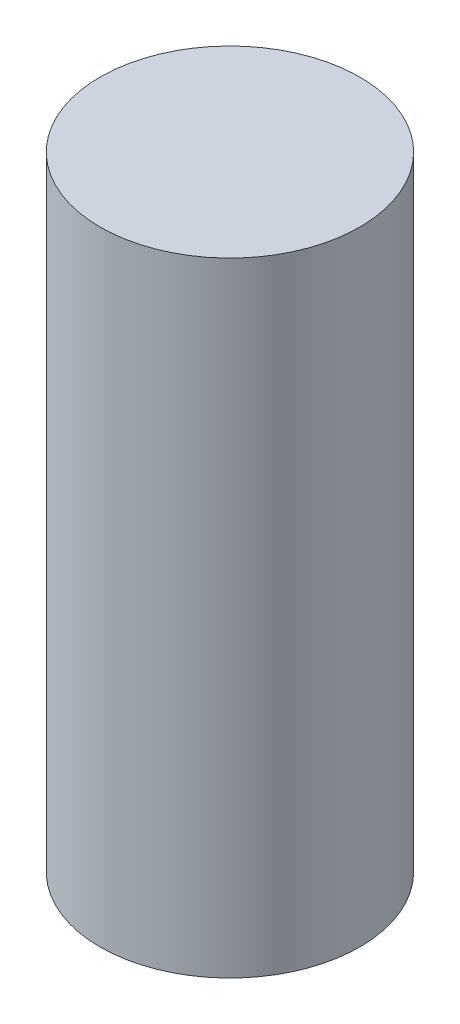
SolidWorks part; units mm, degrees
ref_plane "Front Plane" through (0, 0, 0) normal (0, 0, 1) x (1, 0, 0)
ref_plane "Top Plane" through (0, 0, 0) normal (0, 1, 0) x (1, 0, 0)
ref_plane "Right Plane" through (0, 0, 0) normal (1, 0, 0) x (0, 0, -1)
sketch "Sketch1" plane through (0, 0, 0) normal (0, 1, 0) x (1, 0, 0)
  circle A0 centre (0, 0) radius 10
  dimension "D1" = 20
extrude "Boss-Extrude1" add sketch "Sketch1" along normal blind 48
